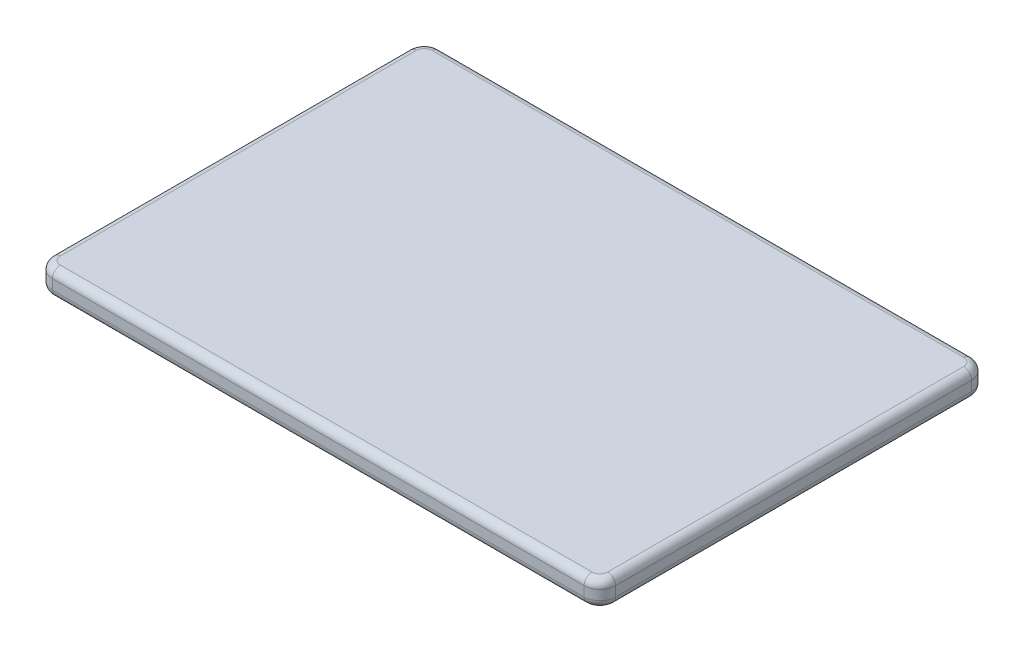
SolidWorks part; units mm, degrees
ref_plane "Front Plane" through (0, 0, 0) normal (0, 0, 1) x (1, 0, 0)
ref_plane "Top Plane" through (0, 0, 0) normal (0, 1, 0) x (1, 0, 0)
ref_plane "Right Plane" through (0, 0, 0) normal (1, 0, 0) x (0, 0, -1)
sketch "Sketch1" plane through (0, 0, 0) normal (0, 1, 0) x (1, 0, 0)
  line L1 (1179.0888, 598.34) -> (820.9488, 598.34)
  line L2 (1179.0888, 598.34) -> (1179.0888, 844.72)
  line L3 (1179.0888, 844.72) -> (820.9488, 844.72)
  line L4 (820.9488, 598.34) -> (820.9488, 844.72)
  dimension "D1" = 358.14
  dimension "D2" = 246.38
extrude "Boss-Extrude1" add sketch "Sketch1" along normal blind 16.256
fillet "Fillet1" radius 10 4 edges at (1179.0888, 8.128, -598.34) (820.9488, 8.128, -598.34) (820.9488, 8.128, -844.72) (1179.0888, 8.128, -844.72)
fillet "Fillet2" radius 5 8 edges at (823.8778, 16.256, -601.2689) (820.9488, 16.256, -721.53) (823.8778, 16.256, -841.791) (1000.0188, 16.256, -844.72) (1176.1599, 16.256, -841.791) (1179.0888, 16.256, -721.53) (1176.1599, 16.256, -601.2689) (1000.0188, 16.256, -598.34)
fillet "Fillet3" radius 5 8 edges at (1176.1599, 0, -841.791) (1179.0888, 0, -721.53) (1176.1599, 0, -601.2689) (1000.0188, 0, -598.34) (823.8778, 0, -601.2689) (820.9488, 0, -721.53) (823.8778, 0, -841.791) (1000.0188, 0, -844.72)
